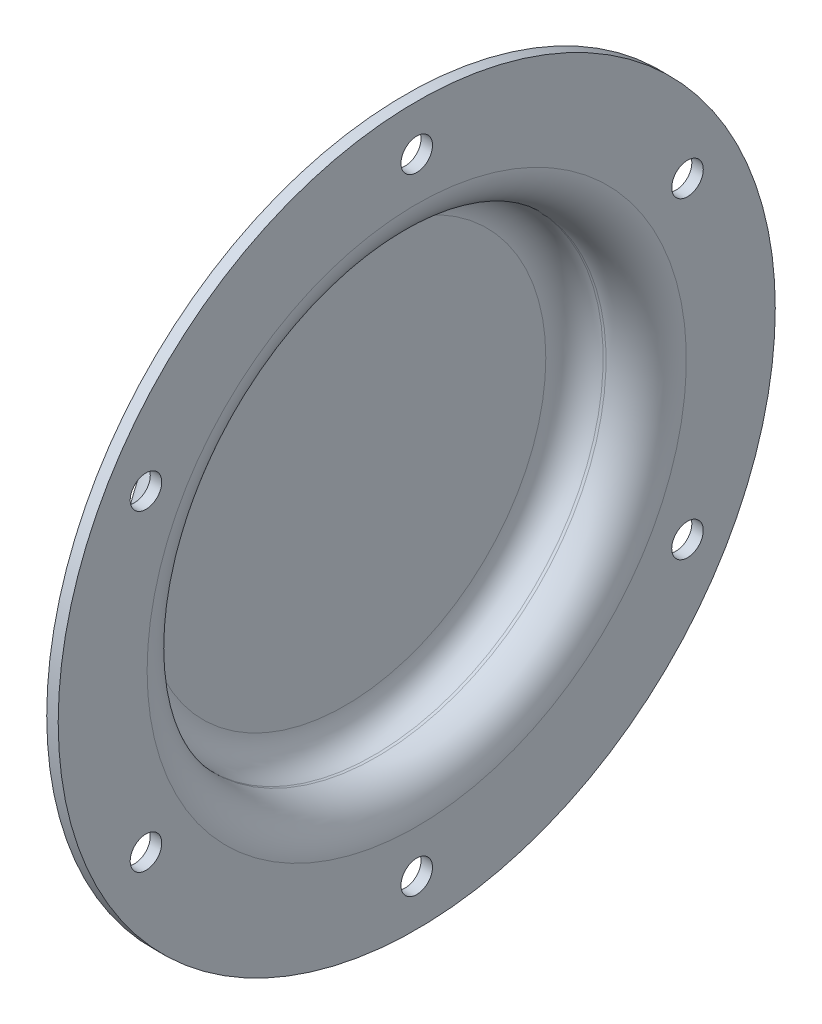
SolidWorks part; units mm, degrees
ref_plane "Front Plane" through (0, 0, 0) normal (0, 0, 1) x (1, 0, 0)
ref_plane "Top Plane" through (0, 0, 0) normal (0, 1, 0) x (1, 0, 0)
ref_plane "Right Plane" through (0, 0, 0) normal (1, 0, 0) x (0, 0, -1)
sketch "Sketch1" plane through (0, 0, 0) normal (0, 0, 1) x (1, 0, 0)
  line L0 (0, 0) -> (0, 70)
  line L1 (10, 80) -> (11, 80)
  line L2 (25, 94) -> (25, 125)
  line L3 (25, 125) -> (21, 125)
  line L4 (21, 125) -> (21, 94)
  line L5 (11, 84) -> (10, 84)
  line L6 (-4, 70) -> (-4, 0)
  line L7 (-4, 0) -> (0, 0)
  arc A0 (21, 94) -> (11, 84) centre (11, 94) cw
  arc A1 (0, 70) -> (10, 80) centre (10, 70) cw
  arc A2 (11, 80) -> (25, 94) centre (11, 94) ccw
  arc A3 (10, 84) -> (-4, 70) centre (10, 70) ccw
  dimension "D7" = 10
  dimension "D8" = 14
  dimension "D1" = 4
  dimension "D2" = 4
  dimension "D3" = 4
  dimension "D4" = 25
  dimension "D5" = 80
  dimension "D6" = 125
revolve "Revolve1" add sketch "Sketch1" angle 360 about L7
sketch "Sketch2" plane through (21, 0, 0) normal (-1, 0, 0) x (0, 0, 1)
  circle A0 centre (0, 109) radius 5.5
  dimension "D1" = 11
  dimension "D2" = 109
extrude "Cut-Extrude1" cut sketch "Sketch2" against normal through all
pattern_circular "CirPattern1" count 6 over 360 about axis through (0, 0, 0) along (1, 0, 0) of "Cut-Extrude1"
